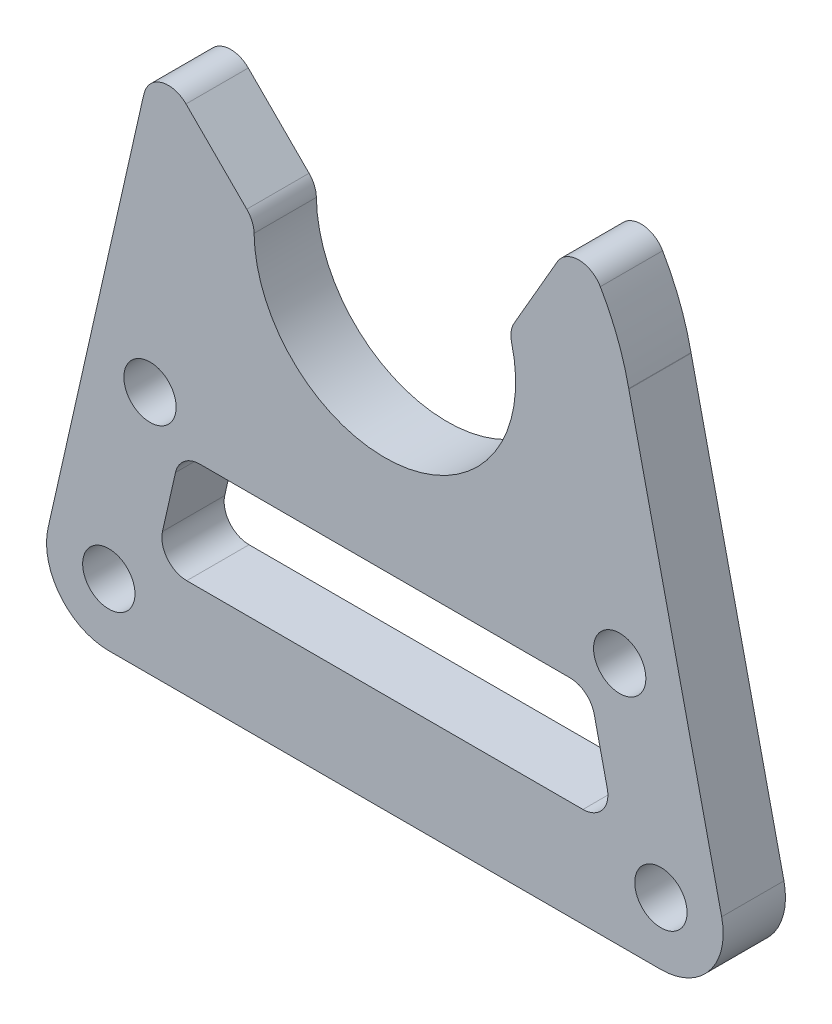
SolidWorks part; units mm, degrees
material "Thornel Mat VMA"
ref_plane "前视基准面" through (0, 0, 0) normal (0, 0, 1) x (1, 0, 0)
ref_plane "上视基准面" through (0, 0, 0) normal (0, 1, 0) x (1, 0, 0)
ref_plane "右视基准面" through (0, 0, 0) normal (1, 0, 0) x (0, 0, -1)
sketch "草图1" plane through (0, 0, 0) normal (0, 0, 1) x (1, 0, 0)
  circle A0 centre (0, 0) radius 10.5
  circle A1 centre (0, 0) radius 20
  dimension "D1" = 21
  dimension "D2" = 40
extrude "凸台-拉伸1" add sketch "草图1" along normal blind 5
sketch "草图2" plane through (0, 0, 5) normal (0, 0, 1) x (1, 0, 0)
  line L5 (28.4156, -35) -> (-28.4156, -35)
  line L10 (-19.4294, 4.7432) -> (-28.4156, -35)
  line L14 (28.4156, -35) -> (19.4294, 4.7432)
  circle A1 centre (0, 0) radius 20
  circle A2 centre (0, 0) radius 20
  arc A4 (19.4294, 4.7432) -> (-19.4294, 4.7432) centre (0, 0) ccw
  circle M9 centre (0, 0) radius 20
  dimension "D2" = 35
  dimension "D1" = 0
extrude "凸台-拉伸2" add sketch "草图2" against normal up to surface (5 mm away) contours L5 L14 L10 M9 up to face at (20, 0, 0)
fillet "圆角1" radius 5 2 edges at (28.4156, -35, 2.5) (-28.4156, -35, 2.5)
sketch "草图3" plane through (0, 0, 5) normal (0, 0, 1) x (1, 0, 0)
  line L0 (-22.1588, -30) -> (-18.8507, -15.3693) construction
  line L1 (22.1588, -30) -> (18.8507, -15.3693) construction
  line L2 (27.0357, -28.8973) -> (19.58, 4.077) construction
  line L3 (-19.58, 4.077) -> (-27.0357, -28.8973) construction
  line L4 (-18.8507, -15.3693) -> (18.8507, -15.3693) construction
  line L5 (22.1588, -30) -> (-22.1588, -30) construction
  line L6 (-16.4533, -18.3693) -> (16.4533, -18.3693)
  line L7 (18.4048, -27) -> (16.4533, -18.3693)
  line L8 (18.4048, -27) -> (-18.4048, -27)
  line L9 (-18.4048, -27) -> (-16.4533, -18.3693)
  circle A0 centre (22.1588, -30) radius 2.1
  circle A1 centre (-22.1588, -30) radius 2.1
  circle A2 centre (-18.8507, -15.3693) radius 2.1
  circle A3 centre (18.8507, -15.3693) radius 2.1
  dimension "D2" = 4.2
  dimension "D1" = 15
  dimension "D3" = 3
extrude "切除-拉伸1" cut sketch "草图3" against normal through all
sketch "草图4" plane through (0, 0, 5) normal (0, 0, 1) x (1, 0, 0)
  line L0 (0, 0) -> (-27.7135, 27.7135) construction
  line L1 (4.925, 4.925) -> (-22.7885, 32.6385)
  line L2 (-4.925, -4.925) -> (-32.6385, 22.7885)
  line L3 (-18.4048, -27) -> (18.4048, -27) construction
  line L4 (0, 0) -> (19.5964, 33.9419) construction
  line L5 (6.0319, -3.4825) -> (25.6283, 30.4594)
  line L6 (-6.0319, 3.4825) -> (13.5645, 37.4244)
  circle A0 centre (0, 0) radius 20
  circle A1 centre (0, 0) radius 10.5
  arc M16 (19.58, 4.077) -> (-19.58, 4.077) centre (0, 0) ccw
  circle M19 centre (0, 0) radius 10.5
  dimension "D3" = 21
  dimension "D4" = 40
  dimension "D5" = 45
  dimension "D6" = 60
  dimension "D7" = 6.965
  dimension "D1" = 6.965
  dimension "D2" = 6.965
  dimension "D8" = 6.965
extrude "切除-拉伸2" cut sketch "草图4" against normal through all contours L6 L1 L2 M19 M16 | L1 L6 M16 | L6 L1 M19 | L6 L1 L5 M19 M16
fillet "圆角2" radius 2 10 edges at (-18.1819, 8.3319, 2.5) (-19.58, 4.077, 2.5) (19.58, 4.077, 2.5) (15.4059, 12.7538, 2.5) (9.9606, 3.3222, 2.5) (-10.481, 0.631, 2.5) (16.4533, -18.3693, 2.5) (18.4048, -27, 2.5) (-18.4048, -27, 2.5) (-16.4533, -18.3693, 2.5)
